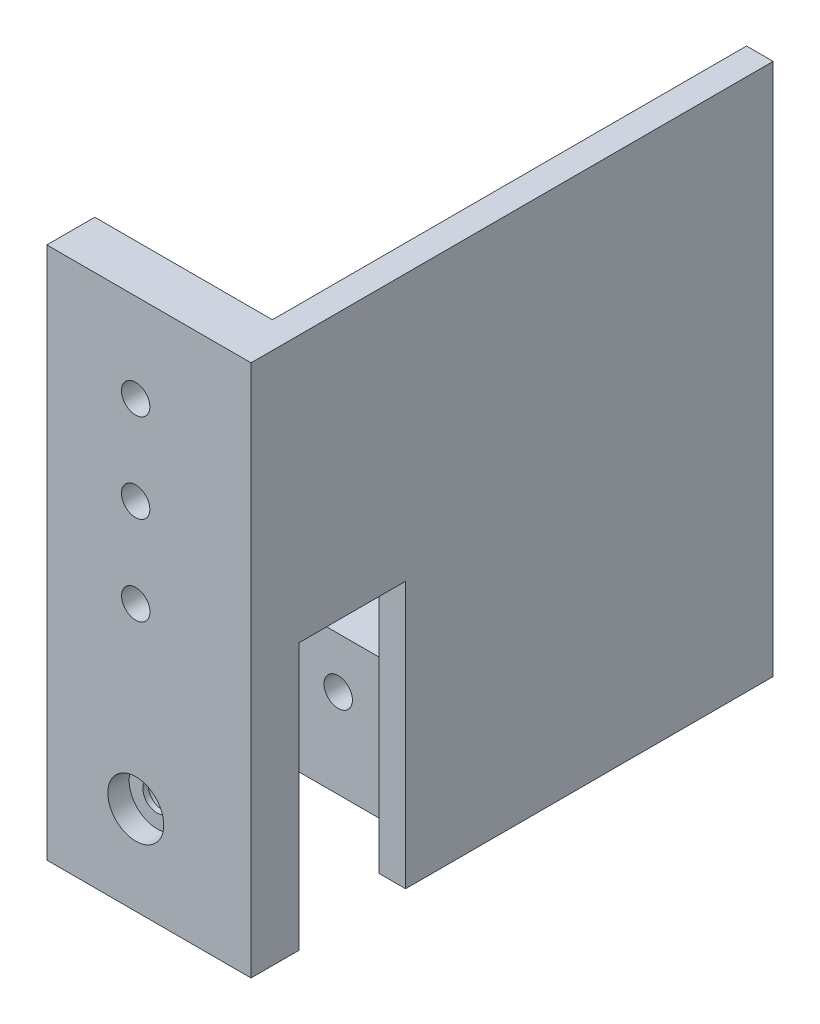
SolidWorks part; units mm, degrees
ref_plane "Front Plane" through (0, 0, 0) normal (0, 0, 1) x (1, 0, 0)
ref_plane "Top Plane" through (0, 0, 0) normal (0, 1, 0) x (1, 0, 0)
ref_plane "Right Plane" through (0, 0, 0) normal (1, 0, 0) x (0, 0, -1)
sketch "Sketch1" plane through (0, 0, 0) normal (0, 0, 1) x (1, 0, 0)
  line L1 (4.6927, -4.5791) -> (33.9027, -4.5791)
  line L2 (4.6927, -4.5791) -> (4.6927, -80.7791)
  line L3 (4.6927, -80.7791) -> (33.9027, -80.7791)
  line L4 (33.9027, -4.5791) -> (33.9027, -80.7791)
  dimension "D1" = 29.21
  dimension "D2" = 76.2
extrude "Boss-Extrude1" add sketch "Sketch1" along normal blind 6.858
sketch "Sketch3" plane through (0, 0, 6.858) normal (0, 0, 1) x (1, 0, 0)
  line L0 (33.9027, -80.7791) -> (33.9027, -4.5791) construction
  line L1 (33.9027, -4.5791) -> (4.6927, -4.5791) construction
  line L2 (17.3927, -4.5791) -> (17.3927, -80.7791) construction
  line L4 (4.6927, -80.7791) -> (33.9027, -80.7791) construction
  circle A0 centre (17.4135, -42.6791) radius 2.032
  circle A1 centre (17.3927, -29.9791) radius 2.032
  circle A2 centre (17.3927, -17.2791) radius 2.032
  dimension "D1" = 12.7
  dimension "D2" = 4.064
  dimension "D3" = 4.064
  dimension "D4" = 4.064
  dimension "D5" = 12.7
  dimension "D6" = 12.7
  dimension "D7" = 16.51
  dimension "D8" = 0
extrude "Cut-Extrude1" cut sketch "Sketch3" against normal blind 25.4
sketch "Sketch4" plane through (0, 0, 6.858) normal (0, 0, 1) x (1, 0, 0)
  circle A1 centre (17.4135, -68.0791) radius 2.032
  circle A3 centre (17.4135, -42.6791) radius 2.032 construction
  dimension "D1" = 25.4
  dimension "D2" = 4.064
sketch "Sketch17" plane through (0, 0, 0) normal (0, 0, -1) x (-1, 0, 0)
  line L0 (-4.6927, -80.7791) -> (-33.9027, -80.7791) construction
  line L1 (-33.9027, -4.5791) -> (-30.0927, -4.5791)
  line L2 (-33.9027, -4.5791) -> (-33.9027, -80.7791)
  line L3 (-33.9027, -80.7791) -> (-30.0927, -80.7791)
  line L4 (-30.0927, -4.5791) -> (-30.0927, -80.7791)
  dimension "D1" = 3.81
extrude "Boss-Extrude13" add sketch "Sketch17" along normal blind 67.818
sketch "Sketch18" plane through (30.0927, 0, 0) normal (-1, 0, 0) x (0, 0, 1)
  line L1 (-67.818, -80.7791) -> (-64.008, -80.7791)
  line L2 (-67.818, -80.7791) -> (-67.818, -60.4591)
  line L3 (-67.818, -60.4591) -> (-64.008, -60.4591)
  line L4 (-64.008, -80.7791) -> (-64.008, -60.4591)
  dimension "D1" = 20.32
  dimension "D2" = 3.81
extrude "Boss-Extrude14" add sketch "Sketch18" along normal blind 25.4
sketch "Sketch19" plane through (30.0927, 0, 0) normal (-1, 0, 0) x (0, 0, 1)
  line L0 (-64.008, -80.7791) -> (0, -80.7791) construction
  line L1 (-22.098, -80.7791) -> (-51.308, -80.7791)
  line L2 (-22.098, -80.7791) -> (-22.098, -60.8301)
  line L3 (-22.098, -60.8301) -> (-51.308, -60.8301)
  line L4 (-51.308, -80.7791) -> (-51.308, -60.8301)
  line L5 (-64.008, -80.7791) -> (-64.008, -60.4591) construction
  dimension "D1" = 12.7
  dimension "D2" = 29.21
extrude "Boss-Extrude15" add sketch "Sketch19" along normal blind 25.4
extrude "Cut-Extrude5" cut sketch "Sketch4" against normal through all contours A1
sketch "Sketch21" plane through (0, 0, 0) normal (0, 0, -1) x (-1, 0, 0)
  circle A0 centre (-17.4135, -68.0791) radius 4
  circle A1 centre (-17.4135, -68.0791) radius 2
  dimension "D1" = 8
  dimension "D2" = 4
extrude "Cut-Extrude6" cut sketch "Sketch21" against normal blind 3.048
sketch "Sketch22" plane through (0, 0, 6.858) normal (0, 0, 1) x (1, 0, 0)
  circle A0 centre (17.4135, -68.0791) radius 4
  dimension "D1" = 8
extrude "Cut-Extrude7" cut sketch "Sketch22" against normal blind 3.048
sketch "Sketch23" plane through (30.0927, 0, 0) normal (-1, 0, 0) x (0, 0, 1)
  line L1 (0, -80.7791) -> (-15.24, -80.7791)
  line L2 (0, -80.7791) -> (0, -42.6791)
  line L3 (0, -42.6791) -> (-15.24, -42.6791)
  line L4 (-15.24, -80.7791) -> (-15.24, -42.6791)
  dimension "D1" = 38.1
  dimension "D2" = 15.24
extrude "Cut-Extrude8" cut sketch "Sketch23" against normal through all
sketch "Sketch24" plane through (0, -80.7791, 0) normal (0, -1, 0) x (1, 0, 0)
  line L1 (6.0824, -24.0843) -> (30.0949, -24.0843)
  line L2 (6.0824, -24.0843) -> (6.0824, -49.5327)
  line L3 (6.0824, -49.5327) -> (30.0949, -49.5327)
  line L4 (30.0949, -24.0843) -> (30.0949, -49.5327)
extrude "Cut-Extrude9" cut sketch "Sketch24" against normal blind 10.16
